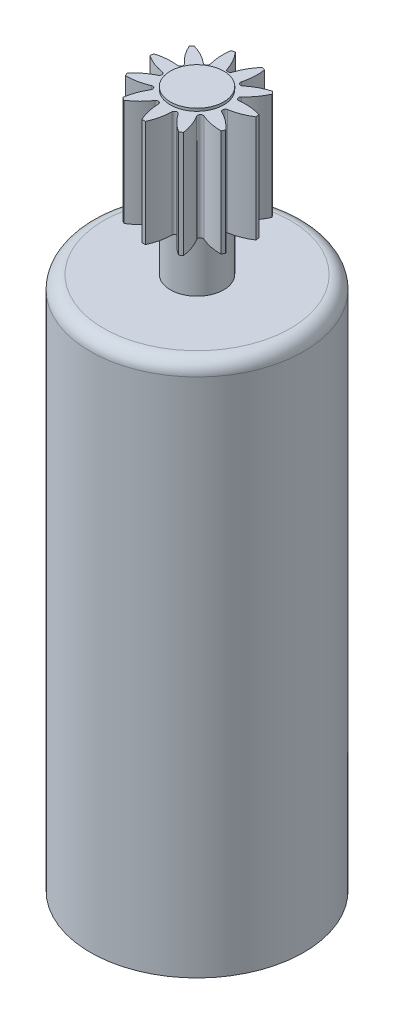
SolidWorks part; units mm, degrees
ref_plane "Front Plane" through (0, 0, 0) normal (0, 0, 1) x (1, 0, 0)
ref_plane "Top Plane" through (0, 0, 0) normal (0, 1, 0) x (1, 0, 0)
ref_plane "Right Plane" through (0, 0, 0) normal (1, 0, 0) x (0, 0, -1)
sketch "Sketch2" plane through (0, 0, 0) normal (0, 0, 1) x (1, 0, 0)
  line L0 (0, 0) -> (0, 26.1)
  line L1 (0, 26.1) -> (1, 26.1)
  line L2 (1, 26.1) -> (1, 26)
  line L3 (1, 26) -> (2, 26)
  line L4 (2, 26) -> (2, 22)
  line L5 (2, 22) -> (1, 22)
  line L6 (1, 22) -> (1, 20)
  line L7 (1, 20) -> (3.5, 20)
  line L8 (4, 19.5) -> (4, 0)
  line L9 (4, 0) -> (0, 0)
  arc A0 (3.5, 20) -> (4, 19.5) centre (3.5, 19.5) cw
  point P13 (4, 20)
  dimension "D9" = 0.5
  dimension "D1" = 26.1
  dimension "D2" = 1
  dimension "D3" = 0.1
  dimension "D4" = 4
  dimension "D5" = 1
  dimension "D6" = 3
  dimension "D7" = 4
  dimension "D8" = 2
revolve "Revolve1" add sketch "Sketch2" angle 360 about L0
sketch "Sketch3" plane through (0, 26, 0) normal (0, 1, 0) x (1, 0, 0)
  line L0 (0, 0) -> (0, 2) construction
  circle A0 centre (0, 0) radius 2 construction
  arc A1 (-0.5, 1.9365) -> (0.5, 1.9365) centre (0, 0) ccw
  arc A2 (0.5, 1.9365) -> (0.0953, 1.2198) centre (2.002, 0.6158) ccw
  arc A3 (0.0953, 1.2198) -> (-0.0953, 1.2198) centre (0, 1.25) cw
  arc A4 (-0.5, 1.9365) -> (-0.0953, 1.2198) centre (-2.002, 0.6158) cw
  arc A5 (-0.5, 1.9365) -> (0.5, 1.9365) centre (0, 0) cw
  circle M7 centre (0, 0) radius 2
  dimension "D2" = 2
  dimension "D3" = 0.1
  dimension "D1" = 1
  dimension "D4" = 0.75
extrude "Cut-Extrude1" cut sketch "Sketch3" against normal blind 6 contours L0 A3 A2 M7 | A3 L0 A5 A4
pattern_circular "CirPattern1" count 11 over 360 about axis through (0, 0, 0) along (0, 1, 0) of "Cut-Extrude1"
